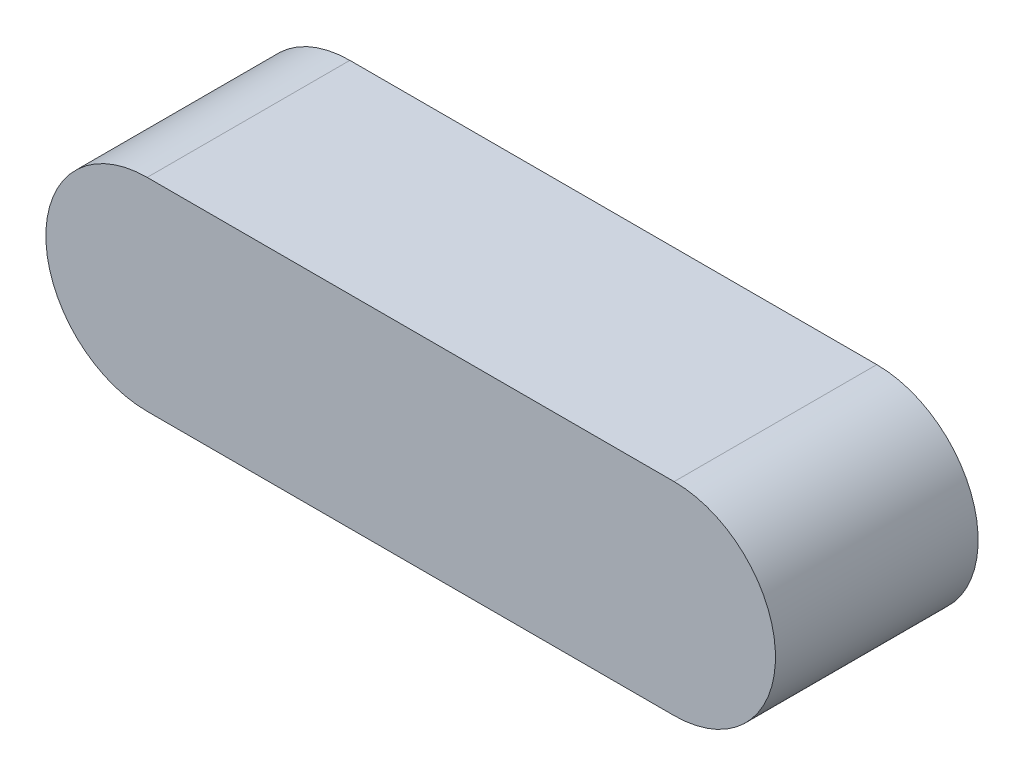
SolidWorks part; units mm, degrees
ref_plane "前视基准面" through (0, 0, 0) normal (0, 0, 1) x (1, 0, 0)
ref_plane "上视基准面" through (0, 0, 0) normal (0, 1, 0) x (1, 0, 0)
ref_plane "右视基准面" through (0, 0, 0) normal (1, 0, 0) x (0, 0, -1)
sketch "草图1" plane through (0, 0, 0) normal (0, 0, 1) x (1, 0, 0)
  line L0 (0, 0) -> (65, 0) construction
  line L1 (0, 12.5) -> (65, 12.5)
  line L2 (0, -12.5) -> (65, -12.5)
  arc A0 (0, 12.5) -> (0, -12.5) centre (0, 0) ccw
  arc A1 (65, -12.5) -> (65, 12.5) centre (65, 0) ccw
  point P3 (32.5, 0)
  dimension "D1" = 12.5
  dimension "D2" = 65
extrude "凸台-拉伸1" add sketch "草图1" along normal blind 25
ref_plane "基准面1" through (0, 0, 0) normal (0, 0, -1) x (-1, 0, 0)
sketch "草图2" plane through (0, 0, 0) normal (0, 0, -1) x (-1, 0, 0)
  line L0 (-32.5, 12.5) -> (-32.5, -12.5) construction
  line L1 (-65, 12.5) -> (0, 12.5) construction
  line L2 (0, -12.5) -> (-65, -12.5) construction
  line L3 (-32.5, 0) -> (-9.75, 0) construction
  circle A0 centre (-9.75, 0) radius 1.5
  circle A1 centre (-55.25, 0) radius 1.5
  dimension "D2" = 3
  dimension "D1" = 22.75
extrude "切除-拉伸1" cut sketch "草图2" against normal blind 5
